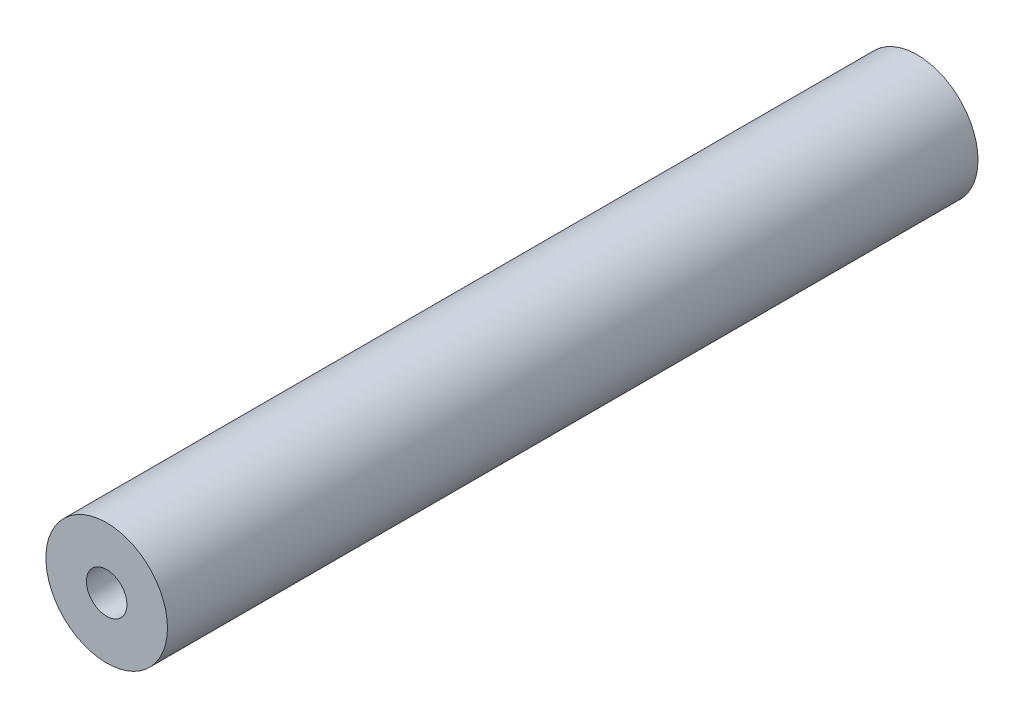
SolidWorks part; units mm, degrees
material "AISI 304"
ref_plane "Front Plane" through (0, 0, 0) normal (0, 0, 1) x (1, 0, 0)
ref_plane "Top Plane" through (0, 0, 0) normal (0, 1, 0) x (1, 0, 0)
ref_plane "Right Plane" through (0, 0, 0) normal (1, 0, 0) x (0, 0, -1)
sketch "Sketch1" plane through (0, 0, 0) normal (0, 0, 1) x (1, 0, 0)
  circle A0 centre (0, 0) radius 4.7625
  dimension "D1" = 9.525
extrude "Boss-Extrude2" add sketch "Sketch1" along normal blind 63.5
sketch "Sketch5" plane through (0, 0, 0) normal (0, 0, 1) x (1, 0, 0)
  circle A0 centre (0, 0) radius 1.5875
  dimension "D1" = 3.175
extrude "Cut-Extrude1" cut sketch "Sketch5" along normal blind 12.7
sketch "Sketch6" plane through (0, 0, 63.5) normal (0, 0, -1) x (-1, 0, 0)
  circle A0 centre (0, 0) radius 1.5875
  dimension "D1" = 3.175
extrude "Cut-Extrude2" cut sketch "Sketch6" along normal blind 12.7
